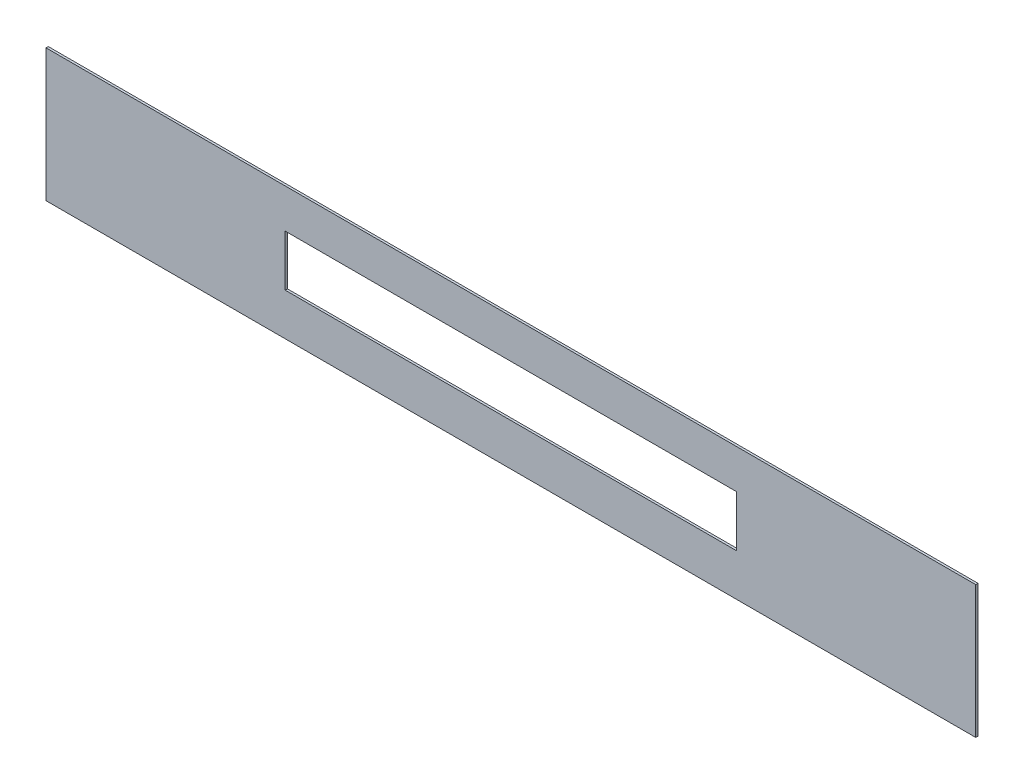
SolidWorks part; units mm, degrees
ref_plane "Front Plane" through (0, 0, 0) normal (0, 0, 1) x (1, 0, 0)
ref_plane "Top Plane" through (0, 0, 0) normal (0, 1, 0) x (1, 0, 0)
ref_plane "Right Plane" through (0, 0, 0) normal (1, 0, 0) x (0, 0, -1)
other "Configuration Table"
sketch "Sketch1" plane through (0, 0, 0) normal (0, 0, 1) x (1, 0, 0)
  line L1 (0, 0) -> (618, 0)
  line L2 (0, 0) -> (0, 88)
  line L3 (0, 88) -> (618, 88)
  line L4 (618, 0) -> (618, 88)
extrude "CEK_donmus_on_dis_sac_1.5_1" add sketch "Sketch1" along normal blind 1.5 from offset 38.5 separate body
sketch "Sketch2" plane through (0, 0, 0) normal (0, 0, 1) x (1, 0, 0)
  line L1 (159, 28) -> (459, 28)
  line L2 (159, 28) -> (159, 62)
  line L3 (159, 62) -> (459, 62)
  line L4 (459, 28) -> (459, 62)
extrude "CEK_donmus_on_dis_sac_1.5_2" cut sketch "Sketch2" along normal blind 14 from offset 27
